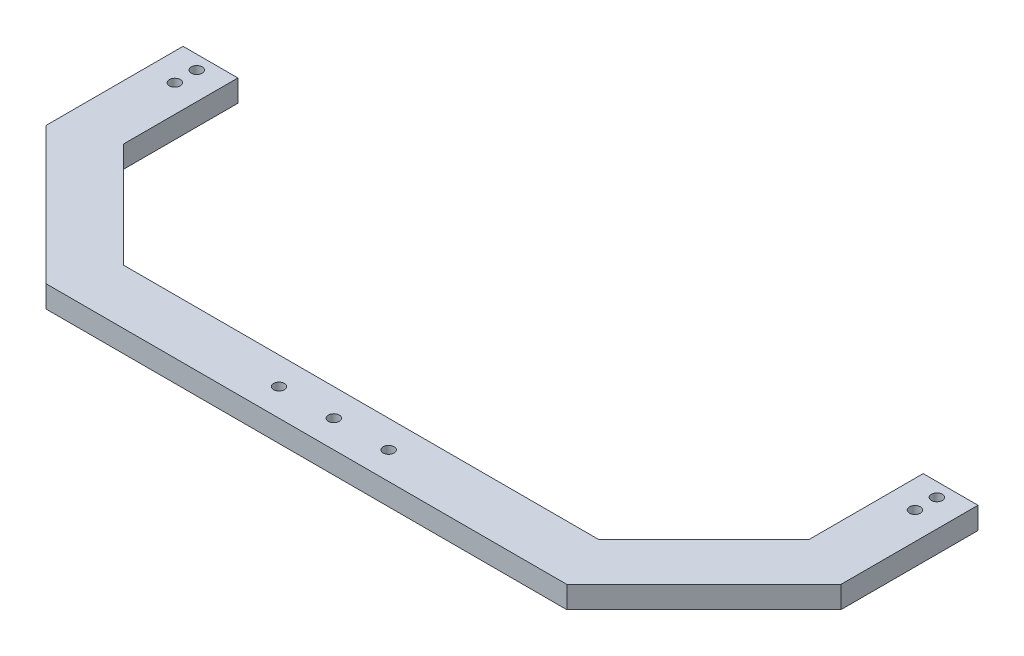
SolidWorks part; units mm, degrees
ref_plane "Front Plane" through (0, 0, 0) normal (0, 0, 1) x (1, 0, 0)
ref_plane "Top Plane" through (0, 0, 0) normal (0, 1, 0) x (1, 0, 0)
ref_plane "Right Plane" through (0, 0, 0) normal (1, 0, 0) x (0, 0, -1)
sketch "Sketch1" plane through (0, 0, 0) normal (0, 1, 0) x (1, 0, 0)
  line L0 (0, 0) -> (0, -50000) construction
  line L1 (0, 0) -> (47.5, 0)
  line L2 (47.5, 0) -> (72.5, 25)
  line L3 (72.5, 25) -> (72.5, 50)
  line L4 (0, 10) -> (43.3579, 10)
  line L5 (43.3579, 10) -> (62.5, 29.1421)
  line L6 (62.5, 29.1421) -> (62.5, 50)
  line L8 (72.5, 50) -> (62.5, 50)
  line L9 (-72.5, 50) -> (-62.5, 50)
  line L10 (-62.5, 29.1421) -> (-62.5, 50)
  line L11 (-43.3579, 10) -> (-62.5, 29.1421)
  line L12 (0, 10) -> (-43.3579, 10)
  line L13 (-72.5, 25) -> (-72.5, 50)
  line L14 (-47.5, 0) -> (-72.5, 25)
  line L15 (0, 0) -> (-47.5, 0)
  circle A0 centre (10, 5) radius 1
  circle A1 centre (0, 5) radius 1
  circle A2 centre (-10, 5) radius 1
  point P3 (-67.5, 50)
  point P11 (0, 0)
  point P16 (0, 0)
  point P19 (67.5, 50)
  dimension "D4" = 2
  dimension "D6" = 25
  dimension "D5" = 5
  dimension "D8" = 10
  dimension "D2" = 135
  dimension "D3" = 50
  dimension "D7" = 45
  dimension "D1" = 10
extrude "Boss-Extrude1" add sketch "Sketch1" along normal blind 4
sketch "Sketch2" plane through (0, 4, 0) normal (0, 1, 0) x (1, 0, 0)
  line L0 (72.5, 50) -> (62.5, 50) construction
  line L1 (0, 0) -> (0, 76.3158) construction
  circle A0 centre (67.5, 47.5) radius 1
  circle A1 centre (67.5, 43.5) radius 1
  circle A2 centre (-67.5, 43.5) radius 1
  circle A3 centre (-67.5, 47.5) radius 1
  point P7 (67.5, 50)
  dimension "D1" = 2
  dimension "D2" = 4
  dimension "D3" = 2.5
extrude "Cut-Extrude1" cut sketch "Sketch2" against normal blind 4
